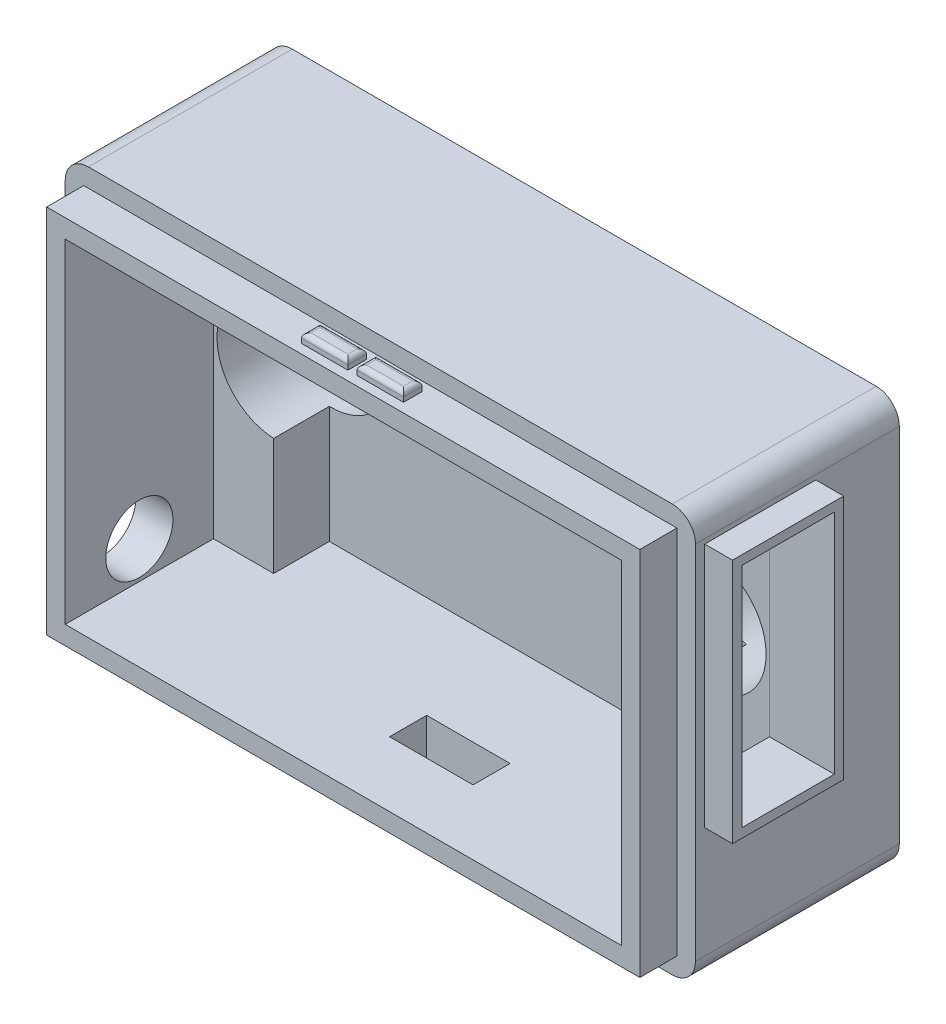
SolidWorks part; units mm, degrees
ref_plane "Front Plane" through (0, 0, 0) normal (0, 0, 1) x (1, 0, 0)
ref_plane "Top Plane" through (0, 0, 0) normal (0, 1, 0) x (1, 0, 0)
ref_plane "Right Plane" through (0, 0, 0) normal (1, 0, 0) x (0, 0, -1)
sketch "Sketch1" plane through (0, 0, 0) normal (0, 0, 1) x (1, 0, 0)
  line L1 (0, 0) -> (68, 0)
  line L2 (0, 0) -> (0, 44)
  line L3 (0, 44) -> (68, 44)
  line L4 (68, 0) -> (68, 44)
  dimension "D1" = 68
  dimension "D2" = 44
extrude "Mian Boss Extrude" add sketch "Sketch1" along normal blind 26
sketch "Sketch2" plane through (0, 0, 26) normal (0, 0, 1) x (1, 0, 0)
  line L0 (68, 44) -> (0, 44) construction
  line L1 (4, 40) -> (64, 40)
  line L2 (4, 40) -> (4, 4)
  line L3 (4, 4) -> (64, 4)
  line L4 (64, 40) -> (64, 4)
  line L5 (0, 0) -> (68, 0) construction
  line L6 (0, 44) -> (0, 0) construction
  line L7 (68, 0) -> (68, 44) construction
  dimension "D1" = 36
  dimension "D2" = 4
  dimension "D3" = 4
  dimension "D4" = 60
  dimension "D5" = 4
  dimension "D6" = 4
extrude "Main cut" cut sketch "Sketch2" against normal blind 16
sketch "Sketch4" plane through (0, 0, 10) normal (0, 0, 1) x (1, 0, 0)
  line L1 (10.5, 39) -> (55.5, 39)
  line L2 (10.5, 39) -> (10.5, 4)
  line L3 (10.5, 4) -> (55.5, 4)
  line L4 (55.5, 39) -> (55.5, 4)
  line L5 (4, 4) -> (64, 4) construction
  line L6 (4, 40) -> (4, 4) construction
  dimension "D1" = 35
  dimension "D2" = 45
  dimension "D3" = 0
  dimension "D4" = 6.5
extrude "Battery Cut" cut sketch "Sketch4" against normal blind 6
sketch "Sketch5" plane through (0, 0, 0) normal (0, 0, -1) x (-1, 0, 0)
  line L0 (-68, 0) -> (-68, 44) construction
  line L1 (0, 44) -> (0, 0) construction
  line L2 (-68, 44) -> (0, 44) construction
  line L3 (0, 0) -> (-68, 0) construction
  circle A0 centre (-57.25, 23) radius 6.375
  circle A1 centre (-10.75, 23) radius 6.375
  dimension "D1" = 12.75
  dimension "D2" = 12.75
  dimension "D4" = 10.75
  dimension "D5" = 21
  dimension "D6" = 21
  dimension "D7" = 10.75
  dimension "D8" = 23
  dimension "D9" = 23
  dimension "D3" = 46.5
extrude "Elctrode Cut" cut sketch "Sketch5" against normal blind 12
sketch "Sketch6" plane through (68, 0, 0) normal (1, 0, 0) x (0, 0, -1)
  line L0 (-26, 0) -> (-26, 44) construction
  line L1 (-20, 40) -> (-10.0107, 40)
  line L2 (-20, 40) -> (-20, 15.5)
  line L3 (-20, 15.5) -> (-10.0107, 15.5)
  line L4 (-10.0107, 40) -> (-10.0107, 15.5)
  line L5 (-26, 44) -> (0, 44) construction
  dimension "D1" = 6
  dimension "D2" = 4
  dimension "D3" = 24.5
extrude "USB-c Cut" cut sketch "Sketch6" against normal blind 7
sketch "Sketch7" plane through (0, 0, 0) normal (-1, 0, 0) x (0, 0, 1)
  line L0 (26, 44) -> (26, 0) construction
  line L1 (26, 44) -> (0, 44) construction
  circle A0 centre (18, 8) radius 3.625
  dimension "D1" = 7.25
  dimension "D3" = 36
  dimension "D2" = 8
extrude "Button Cut" cut sketch "Sketch7" against normal blind 7
sketch "Sketch8" plane through (0, 0, 0) normal (0, -1, 0) x (1, 0, 0)
  line L0 (68, 26) -> (68, 0) construction
  line L1 (32, 19) -> (41, 19)
  line L2 (32, 19) -> (32, 15)
  line L3 (32, 15) -> (41, 15)
  line L4 (41, 19) -> (41, 15)
  line L7 (0, 0) -> (68, 0) construction
  dimension "D1" = 9
  dimension "D2" = 4
  dimension "D3" = 27
  dimension "D4" = 15
extrude "Switch Cut" cut sketch "Sketch8" against normal blind 7
fillet "Outside Fillet" radius 2.5 4 edges at (68, 44, 13) (68, 0, 13) (0, 0, 13) (0, 44, 13)
sketch "Sketch10" plane through (0, 0, 26) normal (0, 0, 1) x (1, 0, 0)
  line L0 (65.5, 44) -> (2.5, 44) construction
  line L1 (2, 2) -> (66, 2)
  line L2 (2, 2) -> (2, 42)
  line L3 (2, 42) -> (66, 42)
  line L4 (66, 2) -> (66, 42)
  line L5 (0, 41.5) -> (0, 2.5) construction
  line L6 (68, 2.5) -> (68, 41.5) construction
  line L7 (2.5, 0) -> (65.5, 0) construction
  dimension "D1" = 2
  dimension "D2" = 2
  dimension "D3" = 2
  dimension "D4" = 2
extrude "Outer lid Extrude" cut sketch "Sketch10" against normal blind 4 flip side to cut
sketch "Sketch11" plane through (0, 2, 0) normal (0, -1, 0) x (1, 0, 0)
  line L0 (2, 26) -> (66, 26) construction
  line L1 (33.5, 23) -> (28.5, 23)
  line L2 (33.5, 23) -> (33.5, 25)
  line L3 (33.5, 25) -> (28.5, 25)
  line L4 (28.5, 23) -> (28.5, 25)
  line L5 (33.5, 23) -> (28.5, 25) construction
  line L6 (33.5, 25) -> (28.5, 23) construction
  line L7 (2, 22) -> (66, 22) construction
  line L8 (39.5, 23) -> (39.5, 25)
  line L13 (2, 22) -> (2, 26) construction
  line L14 (39.5, 23) -> (34.5, 23)
  line L15 (34.5, 23) -> (34.5, 25)
  line L16 (39.5, 25) -> (34.5, 25)
  line L17 (33.5, 23) -> (39.5, 23) construction
  line L18 (66, 22) -> (66, 26) construction
  point P0 (31, 24)
  dimension "D1" = 1
  dimension "D2" = 1
  dimension "D3" = 26.5
  dimension "D4" = 5
  dimension "D5" = 2
  dimension "D7" = 26.5
  dimension "D8" = 2
  dimension "D6" = 5
  dimension "D9" = 6
extrude "Lid Snap-Extrude" add sketch "Sketch11" along normal blind 1 and the other way blind 41
sketch "Sketch13" plane through (0, 0, 25) normal (0, 0, 1) x (1, 0, 0)
  line L1 (28.5, 40) -> (39.5, 40)
  line L2 (28.5, 40) -> (28.5, 4)
  line L3 (28.5, 4) -> (39.5, 4)
  line L4 (39.5, 40) -> (39.5, 4)
extrude "Inner Lid-Extrude" cut sketch "Sketch13" against normal blind 3
sketch "Sketch14" plane through (68, 0, 0) normal (1, 0, 0) x (0, 0, -1)
  line L0 (-10.0107, 40) -> (-20, 40) construction
  line L1 (-21, 41) -> (-9.0107, 41)
  line L2 (-21, 41) -> (-21, 14.5)
  line L3 (-21, 14.5) -> (-9.0107, 14.5)
  line L4 (-9.0107, 41) -> (-9.0107, 14.5)
  line L5 (-10.0107, 15.5) -> (-10.0107, 40) construction
  line L6 (-20, 15.5) -> (-10.0107, 15.5) construction
  line L7 (-20, 40) -> (-20, 15.5) construction
  line L9 (-20, 40) -> (-10.0107, 40)
  line L10 (-20, 40) -> (-20, 15.5)
  line L11 (-20, 15.5) -> (-10.0107, 15.5)
  line L12 (-10.0107, 40) -> (-10.0107, 15.5)
  dimension "D1" = 1
  dimension "D2" = 1
  dimension "D3" = 1
  dimension "D4" = 1
extrude "USB Cover-Extrude" add sketch "Sketch14" along normal blind 3
fillet "Lid Snap Fillet" radius 0.5 16 edges at (34.5, 43, 24) (37, 43, 23) (39.5, 43, 24) (37, 43, 25) (31, 43, 23) (33.5, 43, 24) (31, 43, 25) (28.5, 43, 24) (31, 1, 25) (33.5, 1, 24) (31, 1, 23) (28.5, 1, 24) (39.5, 1, 24) (37, 1, 23) (34.5, 1, 24) (37, 1, 25)
